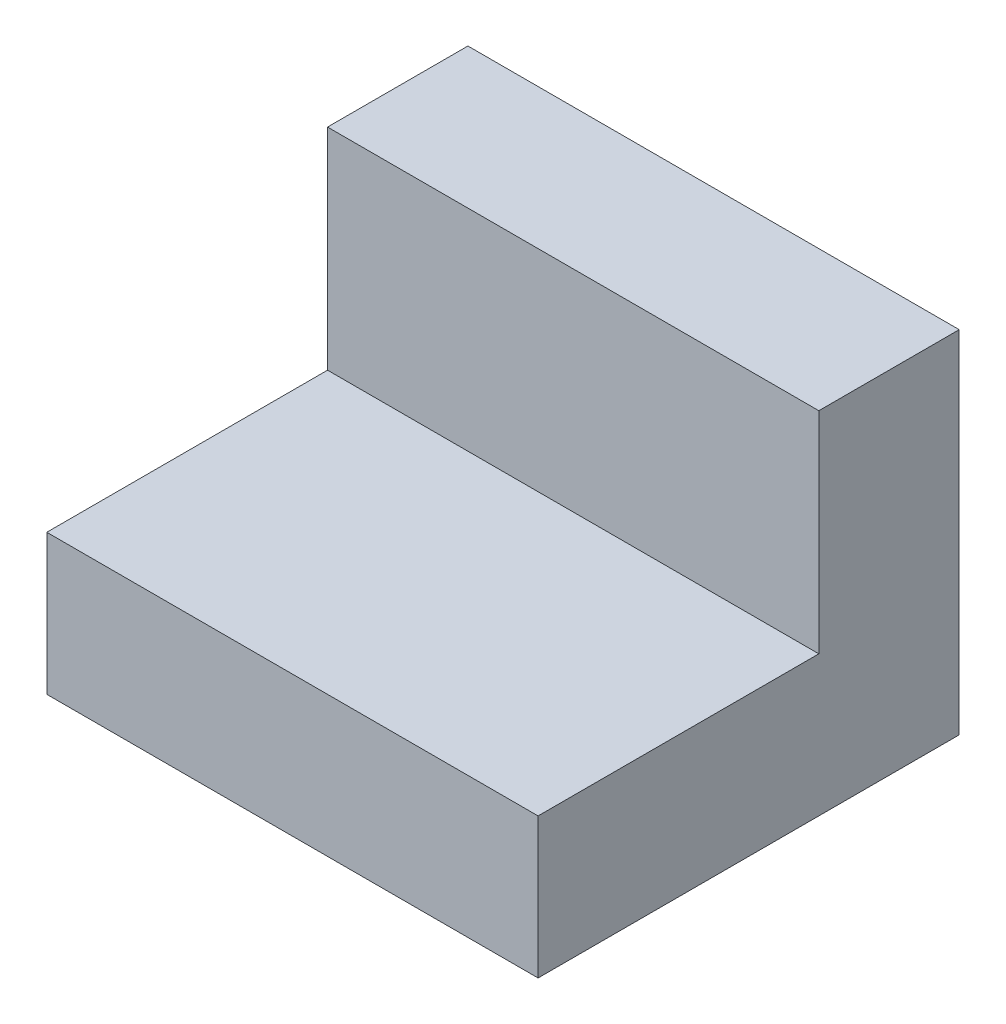
SolidWorks part; units mm, degrees
ref_plane "Plano frontal" through (0, 0, 0) normal (0, 0, 1) x (1, 0, 0)
ref_plane "Plano superior" through (0, 0, 0) normal (0, 1, 0) x (1, 0, 0)
ref_plane "Plano direito" through (0, 0, 0) normal (1, 0, 0) x (0, 0, -1)
sketch "Esboço1" plane through (0, 0, 0) normal (0, 0, 1) x (1, 0, 0)
  line L1 (0, 0) -> (70, 0)
  line L2 (0, 0) -> (0, 20)
  line L3 (0, 20) -> (70, 20)
  line L4 (70, 0) -> (70, 20)
  dimension "D1" = 70
  dimension "D2" = 20
extrude "Ressalto-extrusão1" add sketch "Esboço1" along normal blind 40
sketch "Esboço2" plane through (0, 0, 0) normal (0, 0, -1) x (-1, 0, 0)
  line L1 (-70, 0) -> (0, 0)
  line L2 (-70, 0) -> (-70, 50)
  line L3 (-70, 50) -> (0, 50)
  line L4 (0, 0) -> (0, 50)
  dimension "D1" = 50
  dimension "D2" = 70
extrude "Ressalto-extrusão2" add sketch "Esboço2" along normal blind 20
